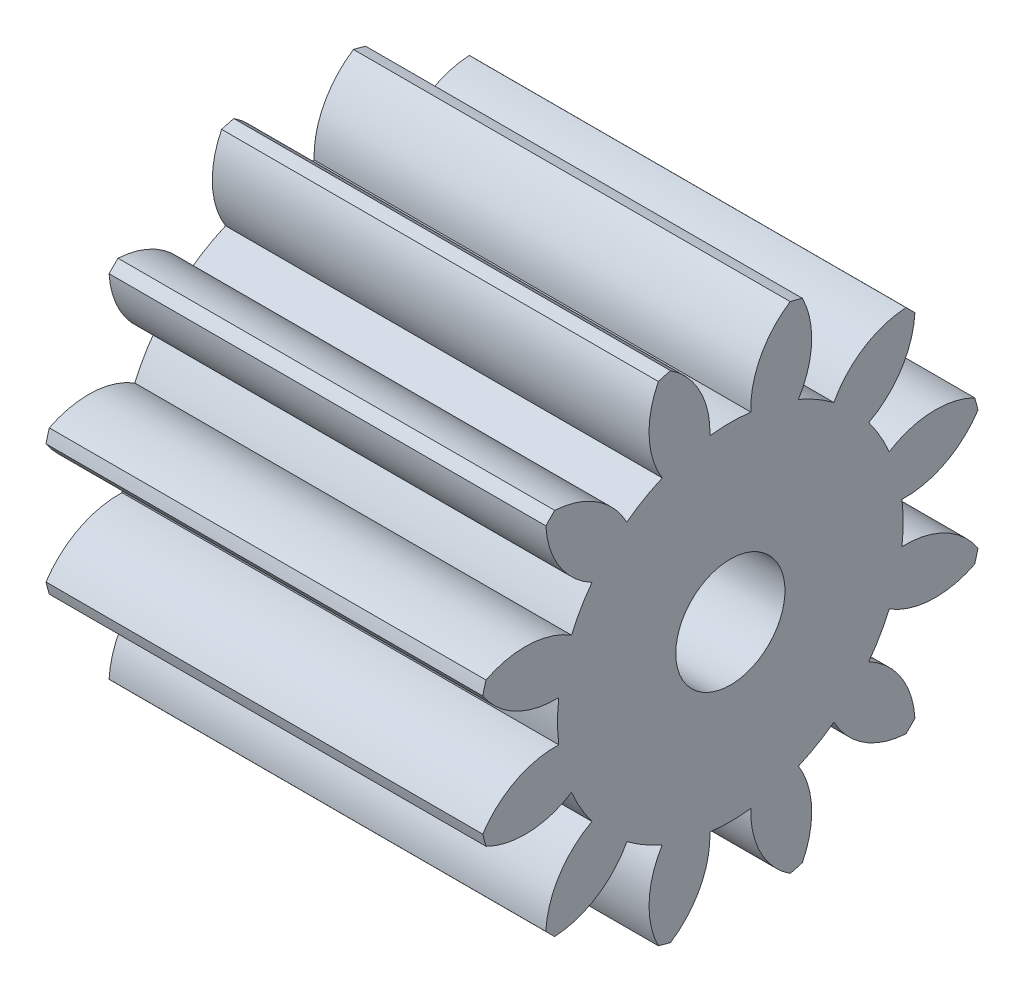
SolidWorks part; units mm, degrees
ref_plane "Plane1" through (0, 0, 0) normal (0, 0, 1) x (1, 0, 0)
ref_plane "Plane2" through (0, 0, 0) normal (0, 1, 0) x (1, 0, 0)
ref_plane "Plane3" through (0, 0, 0) normal (1, 0, 0) x (0, 0, -1)
other "Configuration Table"
sketch "HoldingSke" plane through (0, 0, 0) normal (0, 1, 0) x (1, 0, 0)
  line L0 (0, 0) -> (0.9781, -0.2079)
  line L1 (-15, 0) -> (100, 0) construction
  line L2 (0, 0) -> (-2.1039, 2.3779)
  line L3 (0, 0) -> (-11.863, 4.5341)
  line L4 (0, 0) -> (8.4473, 1.7955)
  line L5 (0, 0) -> (-46.8476, -17.4728)
  line L6 (0, 0) -> (-9.9476, -6.7116)
  line L7 (-2.1039, 2.3779) -> (8.6586, 51.2059)
  line L8 (-76.2, 54.61) -> (-75.7, 54.61)
  line L9 (-71.009, 38.7566) -> (-53.1078, 45.2721)
  line L10 (-76.2, 71.12) -> (104.1128, 71.12)
  line L11 (0, 0) -> (-12, 0)
  line L12 (-76.2, 101.6) -> (-76.162, 101.6)
  line L13 (24.9733, 27.94) -> (52.9518, 28.4284)
  line L14 (24.9733, 27.94) -> (24.9743, 27.94)
  line L15 (24.9733, 27.94) -> (100.4006, 29.5858)
  line L16 (-63.627, -1) -> (-12.827, -1)
  circle A0 centre (0, 0) radius 1.5
  circle A1 centre (0, 0) radius 4.749
  circle A2 centre (0, 0) radius 37.5
  circle A3 centre (0, 0) radius 1.5
  dimension "MHD" = 9.498
  dimension "Hub_dia" = 75
  dimension "Bore" = 3
  dimension "MBD" = 3
  dimension "Num_teeth" = 12
  dimension "Pitch" = 1
  dimension "Overall_len" = 50
  dimension "Show_teeth" = 12
  dimension "Thickness" = 12
  dimension "OAL" = 50.0001
  dimension "T_dim" = 0.5
  dimension "Ap" = 20
  dimension "H" = 19.05
  dimension "Pitch_radius" = 180.3128
  dimension "Width" = 12
  dimension "Backlash" = 0.038
  dimension "Addendum_fac" = 1
  dimension "Dedendum_fac" = 1.25
  dimension "Clearance_fac" = 0.25
  dimension "Dedendum_add" = 0.001
  dimension "Module" = 1
sketch "BasProSke" plane through (0, 0, 0) normal (0, 1, 0) x (1, 0, 0)
  line L0 (-10, 0) -> (60, 0) construction
  line L1 (0, 0) -> (0, 7)
  line L2 (0, 0) -> (12, 0)
  line L3 (12, 0) -> (12, 7)
  line L4 (12, 7) -> (0, 7)
  dimension "Thickness" = 12
  dimension "Diameter" = 14
revolve "Base-Revolve" add sketch "BasProSke" angle 360 about L0
sketch "TooCutSke" plane through (0, 0, 0) normal (1, 0, 0) x (0, 0, -1)
  line L1 (0, 0) -> (0, 107) construction
  line L2 (0, 0) -> (-0.8496, 5.9395) construction
  line L3 (0, 0) -> (-3.0836, 11.5081) construction
  line L4 (-0.8496, 5.9395) -> (-1.5418, 5.7541) construction
  arc A0 (0.5622, 4.7156) -> (-0.5622, 4.7156) centre (0, 0) ccw
  arc A1 (1.6729, 6.8233) -> (-1.6729, 6.8233) centre (0, 0) ccw
  circle A2 centre (0, 0) radius 6 construction
  circle A3 centre (0, 0) radius 5.6382 construction
  arc A4 (-0.5622, 4.7156) -> (-1.6729, 6.8233) centre (-2.9608, 4.7982) ccw
  arc A5 (1.6729, 6.8233) -> (0.5622, 4.7156) centre (2.9608, 4.7982) ccw
  dimension "Root_dia" = 9.498
  dimension "Overcut_dia" = 14.0508
  dimension "Pitch_dia" = 12
  dimension "Base_dia" = 11.2763
  dimension "Flank_rad" = 2.4
  dimension "Half_ang" = 15
  dimension "Half_CT" = 0.7167
extrude "ToothCut" cut sketch "TooCutSke" along normal through all
fillet "Breaks" [suppressed] radius 0.02
fillet "RootFillets" [suppressed] radius 0.251
pattern_circular "TeethCuts" count 12 every 30 about axis through (-10, 0, 0) along (1, 0, 0) of "ToothCut", "RootFillets", "Breaks"
sketch "HubNeaOneSke" plane through (0, 0, 0) normal (-1, 0, 0) x (0, 0, 1)
  circle A0 centre (0, 0) radius 4.749
  dimension "Diameter" = 9.498
extrude "HubNearOne" [suppressed] add sketch "HubNeaOneSke" along normal blind 38.0001
sketch "HubNeaBotSke" plane through (0, 0, 0) normal (-1, 0, 0) x (0, 0, 1)
  circle A0 centre (0, 0) radius 4.749
  dimension "Diameter" = 9.498
extrude "HubNearBoth" [suppressed] add sketch "HubNeaBotSke" along normal blind 19
ref_plane "FarPln" through (12, 0, 0) normal (1, 0, 0) x (0, 0, -1)
sketch "HubFarSke" plane through (12, 0, 0) normal (1, 0, 0) x (0, 0, -1)
  circle A0 centre (0, 0) radius 4.749
  dimension "Diameter" = 9.498
extrude "HubFar" [suppressed] add sketch "HubFarSke" along normal blind 19
sketch "BorSke" plane through (0, 0, 0) normal (1, 0, 0) x (0, 0, -1)
  circle A0 centre (0, 0) radius 1.5
  dimension "Diameter" = 3
extrude "Bore" cut sketch "BorSke" along normal mid plane 100.0001
sketch "KeySke" plane through (0, 0, 0) normal (1, 0, 0) x (0, 0, -1)
  line L0 (-0.6, 0) -> (-0.6, 2)
  line L1 (-0.6, 2) -> (0.6, 2)
  line L2 (0.6, 2) -> (0.6, 0)
  line L3 (0, 0) -> (0, 34) construction
  line L4 (-0.6, 0) -> (0.6, 0)
  dimension "Offset" = 2
extrude "Keyway" [suppressed] cut sketch "KeySke" along normal mid plane 100.0001
pattern_circular "Keyway2" [suppressed] count 2 every 90 about axis through (-10, 0, 0) along (1, 0, 0)
equation "' \"Module@HoldingSke\" = 6.35"
equation "' \"Num_teeth@HoldingSke\" = 12"
equation "' \"Ap@HoldingSke\" =  20"
equation "' \"Ap@HoldingSke\" = 20"
equation "' \"Width@HoldingSke\" = 0.5 * 25.4"
equation "' \"Hub_dia@HoldingSke\"= 1 * 25.4"
equation "' \"Hub_dia@HoldingSke\" = 1 * 25.4"
equation "' \"Overall_len@HoldingSke\" = 1.0 * 25.4"
equation "' \"Bore@HoldingSke\" = 0.75 * 25.4"
equation "' \"T_dim@HoldingSke\" = 0.1 * 25.4"
equation "' \"Width@KeySke\" = 0.25 * 25.4"
equation "' \"Show_teeth@HoldingSke\" = 13"
equation "' \"Backlash@HoldingSke\" = 0.009 * 25.4"
equation "' \"Addendum_fac@HoldingSke\" = 1.0"
equation "' \"Dedendum_fac@HoldingSke\" = 1.25"
equation "' \"Dedendum_add@HoldingSke\" = 0.00005 * 25.4"
equation "' \"Clearance_fac@HoldingSke\" = 0.25"
equation "\"Pitch@HoldingSke\" = 1 / \"Module@HoldingSke\""
equation "\"Overcut_dia@TooCutSke\" = (\"Num_teeth@HoldingSke\" + 2 * \"Addendum_fac@HoldingSke\") / \"Pitch@HoldingSke\" + 0.002 * 25.4"
equation "\"Pitch_dia@TooCutSke\" = \"Num_teeth@HoldingSke\" / \"Pitch@HoldingSke\""
equation "\"Base_dia@TooCutSke\" = \"Num_teeth@HoldingSke\" / \"Pitch@HoldingSke\" * cos((\"Ap@HoldingSke\"  * 3.14159265 / 180))"
equation "\"Root_dia@TooCutSke\" = (\"Num_teeth@HoldingSke\" + 2) / \"Pitch@HoldingSke\" - 2 * (\"Addendum_fac@HoldingSke\" + \"Dedendum_fac@HoldingSke\") / \"Pitch@HoldingSke\" - \"Dedendum_add@HoldingSke\" * 2"
equation "\"Half_ang@TooCutSke\" = 180 / \"Num_teeth@HoldingSke\""
equation "\"Half_CT@TooCutSke\" = \"Num_teeth@HoldingSke\" / \"Pitch@HoldingSke\" * sin((3.14159265 / 2 / \"Num_teeth@HoldingSke\")) / 2 - 7 * \"Backlash@HoldingSke\" / 4"
equation "\"Flank_rad@TooCutSke\" = \"Num_teeth@HoldingSke\" / \"Pitch@HoldingSke\" / 5"
equation "\"Radius@RootFillets\" = \"Clearance_fac@HoldingSke\" / \"Pitch@HoldingSke\" + \"Dedendum_add@HoldingSke\""
equation "\"Break_rad@Breaks\" = 0.02 / \"Pitch@HoldingSke\""
equation "\"Thickness@HoldingSke\" = \"Width@HoldingSke\""
equation "\"OAL@HoldingSke\" = \"Thickness@HoldingSke\""
equation "\"MHD@HoldingSke\" = (\"Num_teeth@HoldingSke\" + 2) / \"Pitch@HoldingSke\" - 2 * (\"Addendum_fac@HoldingSke\" + \"Dedendum_fac@HoldingSke\")  / \"Pitch@HoldingSke\" - \"Dedendum_add@HoldingSke\" * 2"
equation "\"MBD@HoldingSke\" = (\"Num_teeth@HoldingSke\" + 2) / \"Pitch@HoldingSke\" - 2 * (\"Addendum_fac@HoldingSke\" + \"Dedendum_fac@HoldingSke\")  / \"Pitch@HoldingSke\" - \"Dedendum_add@HoldingSke\" * 2 - 0.002 * 25.4"
equation "\"MHD@HoldingSke\" = ((sgn( \"MHD@HoldingSke\" - \"Hub_dia@HoldingSke\" )-1)*( \"MHD@HoldingSke\" - \"Hub_dia@HoldingSke\" ))/-2+ \"Hub_dia@HoldingSke\""
equation "\"MBD@HoldingSke\" = ((sgn( \"MBD@HoldingSke\" - \"Bore@HoldingSke\" )-1)*( \"MBD@HoldingSke\" - \"Bore@HoldingSke\" ))/-2+ \"Bore@HoldingSke\""
equation "\"OAL@HoldingSke\" = ((sgn( \"OAL@HoldingSke\" - \"Overall_len@HoldingSke\" )+1)*( \"OAL@HoldingSke\" - \"Overall_len@HoldingSke\" ))/2 + \"Overall_len@HoldingSke\" + 0.000002 * 25.4"
equation "\"Num_teeth@TeethCuts\" = int( \"Show_teeth@HoldingSke\" ) + 1"
equation "\"Num_teeth@TeethCuts\" = ((sgn( \"Num_teeth@TeethCuts\" - \"Num_teeth@HoldingSke\" )-1)*( \"Num_teeth@TeethCuts\" - \"Num_teeth@HoldingSke\" ))/-2+ \"Num_teeth@HoldingSke\""
equation "\"Num_teeth@TeethCuts\" = ((sgn( \"Num_teeth@TeethCuts\" - 2.0)+1)*( \"Num_teeth@TeethCuts\" - 2.0))/2 +2.0"
equation "\"Angle@TeethCuts\" = 360.0 / \"Num_teeth@HoldingSke\""
equation "\"Diameter@BasProSke\" = (\"Num_teeth@HoldingSke\" + 2 * \"Addendum_fac@HoldingSke\") / \"Pitch@HoldingSke\""
equation "\"Thickness@BasProSke\"  = \"Thickness@HoldingSke\""
equation "' \"Fillet_rad@BasProSke\" =  \"Thickness@HoldingSke\" * 0.05"
equation "' \"Fillet_rad@BasProSke\" = \"Thickness@HoldingSke\" * 0.05"
equation "\"MHD@HoldingSke\" = ((sgn( \"MHD@HoldingSke\" - \"Root_dia@TooCutSke\" )-1)*( \"MHD@HoldingSke\" - \"Root_dia@TooCutSke\" ))/-2+ \"Root_dia@TooCutSke\""
equation "\"Diameter@HubNeaOneSke\" = \"MHD@HoldingSke\""
equation "\"Length@HubNearOne\" = \"OAL@HoldingSke\" - \"Thickness@BasProSke\""
equation "\"Diameter@HubNeaBotSke\" = \"MHD@HoldingSke\""
equation "\"Length@HubNearBoth\" = ( \"OAL@HoldingSke\" - \"Thickness@BasProSke\" ) / 2.0"
equation "\"Thickness@FarPln\" = \"Thickness@BasProSke\""
equation "\"Diameter@HubFarSke\" = \"MHD@HoldingSke\""
equation "\"Length@HubFar\" = ( \"OAL@HoldingSke\" - \"Thickness@BasProSke\" ) / 2.0"
equation "\"Diameter@BorSke\" = \"MBD@HoldingSke\""
equation "\"D1@Bore\" = \"OAL@HoldingSke\" * 2.0"
equation "\"D1@Keyway\" = \"OAL@HoldingSke\" * 2.0"
equation "\"Offset@KeySke\" = \"T_dim@HoldingSke\" + \"MBD@HoldingSke\" / 2.0"
